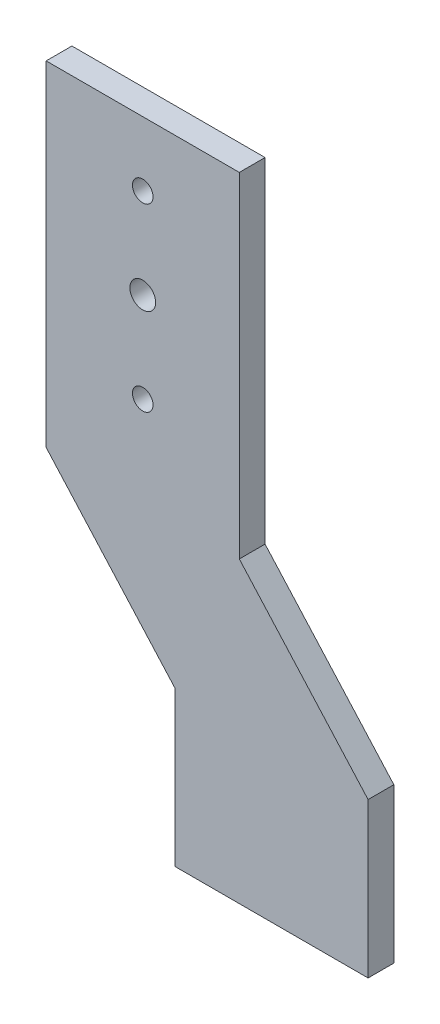
SolidWorks part; units mm, degrees
ref_plane "Front Plane" through (0, 0, 0) normal (0, 0, 1) x (1, 0, 0)
ref_plane "Top Plane" through (0, 0, 0) normal (0, 1, 0) x (1, 0, 0)
ref_plane "Right Plane" through (0, 0, 0) normal (1, 0, 0) x (0, 0, -1)
sketch "Sketch1" plane through (0, 0, 0) normal (0, 0, 1) x (1, 0, 0)
  line L0 (0, 0) -> (0, 171.5278) construction
  line L1 (0, 0) -> (150, 0) construction
  line L2 (0, 245.9017) -> (75, 245.9017)
  line L3 (75, 245.9017) -> (75, 115.9017)
  line L4 (75, 115.9017) -> (125, 60)
  line L5 (125, 60) -> (125, 0)
  line L6 (125, 0) -> (50, 0)
  line L7 (50, 0) -> (50, 60)
  line L8 (50, 60) -> (0, 115.9017)
  line L9 (0, 115.9017) -> (0, 245.9017)
  dimension "D1" = 75
  dimension "D2" = 130
  dimension "D3" = 60
  dimension "D4" = 60
  dimension "D5" = 75
  dimension "D6" = 50
  dimension "D7" = 130
extrude "Boss-Extrude1" add sketch "Sketch1" along normal blind 10
sketch "Sketch2" plane through (0, 0, 10) normal (0, 0, 1) x (1, 0, 0)
  line L0 (75, 245.9017) -> (0, 245.9017) construction
  line L1 (0, 245.9017) -> (0, 115.9017) construction
  point P0 (37.5, 220.9017)
  point P1 (37.5, 185.9017)
  point P2 (37.5, 150.9017)
  point P18 (37.5, 220.9017)
  point P20 (37.5, 150.9017)
  point P23 (0, 0)
  point P24 (0, 0)
  point P25 (0, 0)
  dimension "D1" = 35
  dimension "D2" = 35
  dimension "D3" = 25
  dimension "D4" = 37.5
hole_wizard "Ø8.0mm Dowel Hole5" positions "Sketch2" profile "Sketch11" hole size "Ø8.0" standard "ANSI Metric"
sketch "Sketch11" plane through (37.5, 220.9017, 10) normal (1, 0, 0) x (0, -1, 0)
  line L0 (0, 0) -> (0, 10)
  line L1 (0, 10) -> (4, 10)
  line L2 (4, 10) -> (4, 0)
  line L5 (4, 0) -> (0, 0)
  line L11 (0, -6.35) -> (0, 107.95) construction
  dimension "Thru Hole Dia." = 8
  dimension "Thru Hole Depth" = 10
sketch "Sketch13" plane through (0, 0, 10) normal (0, 0, 1) x (1, 0, 0)
  line L0 (0, 245.9017) -> (0, 115.9017) construction
  line L1 (75, 245.9017) -> (0, 245.9017) construction
  point P0 (37.5, 185.9017)
  dimension "D1" = 37.5
  dimension "D2" = 60
hole_wizard "Ø10.0mm Dowel Hole1" positions "Sketch13" profile "Sketch14" hole size "Ø10.0" standard "ANSI Metric" end condition through all
sketch "Sketch14" plane through (37.5, 185.9017, 10) normal (1, 0, 0) x (0, -1, 0)
  line L0 (0, 0) -> (0, 10)
  line L1 (0, 10) -> (5, 10)
  line L2 (5, 10) -> (5, 0)
  line L5 (5, 0) -> (0, 0)
  line L11 (0, -6.35) -> (0, 107.95) construction
  dimension "Thru Hole Dia." = 10
  dimension "Thru Hole Depth" = 10
